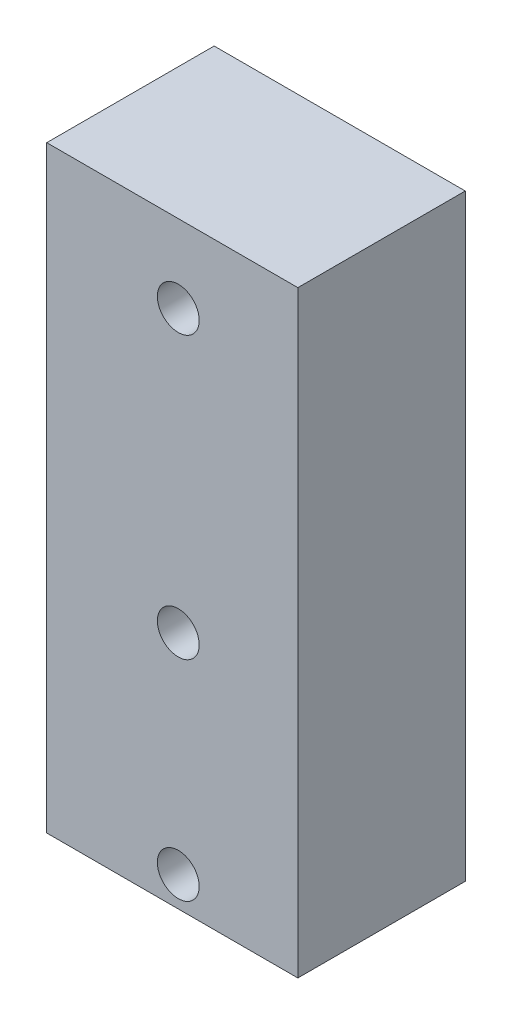
SolidWorks part; units mm, degrees
ref_plane "Front Plane" through (0, 0, 0) normal (0, 0, 1) x (1, 0, 0)
ref_plane "Top Plane" through (0, 0, 0) normal (0, 1, 0) x (1, 0, 0)
ref_plane "Right Plane" through (0, 0, 0) normal (1, 0, 0) x (0, 0, -1)
sketch "Sketch1" plane through (0, 0, 0) normal (0, 1, 0) x (1, 0, 0)
  line L0 (-11, 11.0455) -> (-11, -2.9545)
  line L1 (-11, -2.9545) -> (10, -2.9545)
  line L3 (-11, 11.0455) -> (10, 11.0455)
  line L4 (10, -2.9545) -> (10, 11.0455)
  point P1 (0, 0)
  dimension "D1" = 10
  dimension "D2" = 11
  dimension "D3" = 11.0455
  dimension "D4" = 2.9545
extrude "Boss-Extrude1" add sketch "Sketch1" along normal blind 50
ref_plane "Plane1" through (0, 0, 2.9545) normal (0, 0, 1) x (1, 0, 0)
sketch "Sketch2" plane through (0, 0, 2.9545) normal (0, 0, 1) x (1, 0, 0)
  circle A0 centre (0, 2.5) radius 1.75
  circle A1 centre (0, 20) radius 1.75
  dimension "D1" = 3.5
  dimension "D2" = 2.5
  dimension "D3" = 20
extrude "Cut-Extrude1" cut sketch "Sketch2" against normal blind 100
sketch "Sketch3" plane through (0, 0, -11.0455) normal (0, 0, -1) x (-1, 0, 0)
  line L0 (0, 20) -> (0, 43.5)
  line L1 (-10, 0) -> (11, 0) construction
  circle A0 centre (0, 43.5) radius 1.75
  dimension "D1" = 3.5
  dimension "D2" = 43.5
extrude "Cut-Extrude2" cut sketch "Sketch3" against normal blind 22
